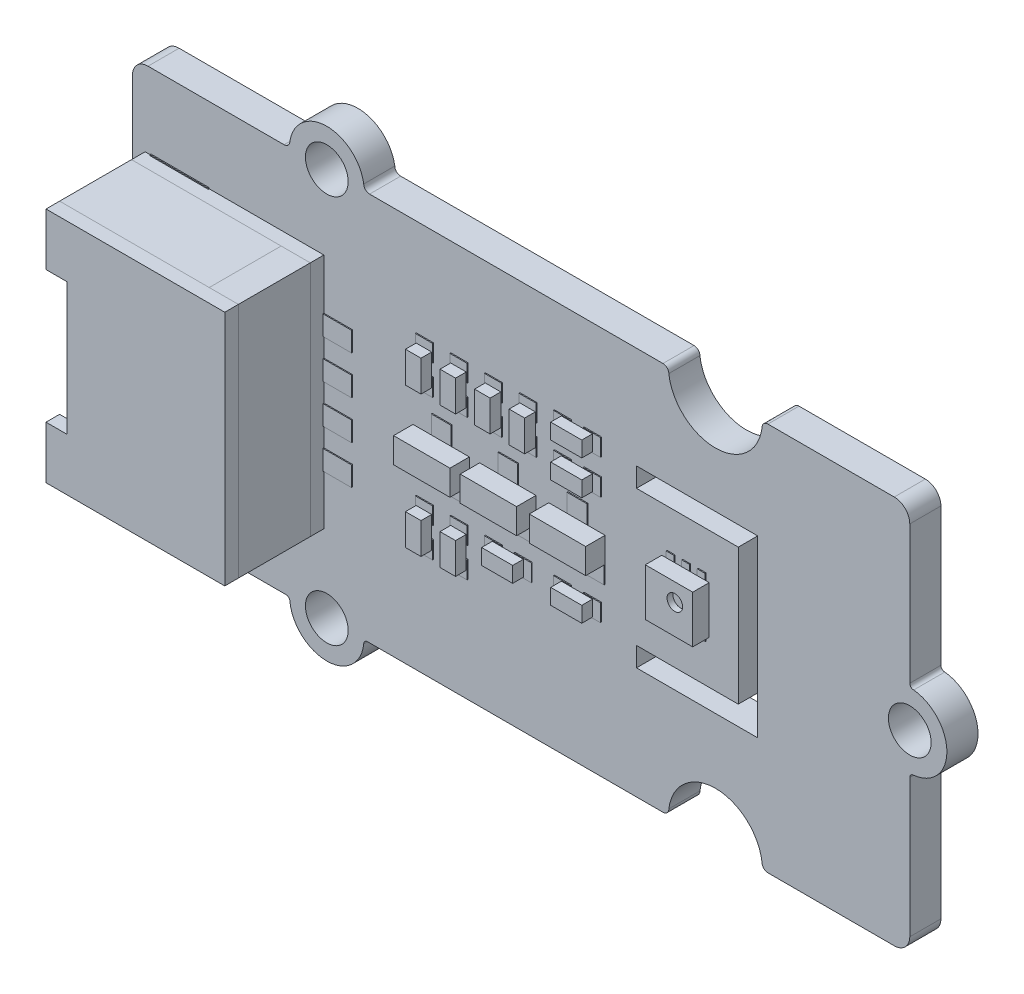
SolidWorks part; units mm, degrees
other "Carte_Grove_101021095"
other "Capteur_SGP40"
ref_plane "Plan de face" through (0, 0, 0) normal (0, 0, 1) x (1, 0, 0)
ref_plane "Plan de dessus" through (0, 0, 0) normal (0, 1, 0) x (1, 0, 0)
ref_plane "Plan de droite" through (0, 0, 0) normal (1, 0, 0) x (0, 0, -1)
sketch "Esquisse1" plane through (0, 0, 0) normal (0, 0, 1) x (1, 0, 0)
  line L0 (19.365, -9.2) -> (19.365, -2.1)
  line L1 (19.365, 2.1) -> (19.365, 9.2)
  line L2 (18.565, 10) -> (12.065, 10)
  line L3 (-19.835, -10) -> (-12.735, -10)
  line L4 (-19.835, 10) -> (-12.835, 10)
  line L5 (-8.435, 10) -> (6.665, 10)
  line L6 (6.665, -10) -> (-8.535, -10)
  line L7 (12.065, -10) -> (18.565, -10)
  line L8 (-20.635, -2.7) -> (-20.635, -9.2)
  line L9 (-20.635, 2.7) -> (-20.635, 9.2)
  line L10 (5.301, 3.754) -> (10.539, 3.754)
  line L11 (10.539, 3.754) -> (10.539, -3.246)
  line L12 (10.539, -3.246) -> (5.301, -3.246)
  line L13 (5.301, -3.246) -> (5.301, -4.246)
  line L14 (5.301, -4.246) -> (11.539, -4.246)
  line L15 (11.539, -4.246) -> (11.539, 4.754)
  line L16 (11.539, 4.754) -> (5.301, 4.754)
  line L17 (5.301, 4.754) -> (5.301, 3.754)
  arc A0 (-19.835, 10) -> (-20.635, 9.2) centre (-19.835, 9.2) ccw
  arc A1 (-20.635, -9.2) -> (-19.835, -10) centre (-19.835, -9.2) ccw
  arc A2 (18.565, -10) -> (19.365, -9.2) centre (18.565, -9.2) ccw
  arc A3 (19.365, 9.2) -> (18.565, 10) centre (18.565, 9.2) ccw
  arc A4 (12.065, 10) -> (11.765, 9.7) centre (12.065, 9.7) ccw
  arc A5 (-12.735, -10) -> (-12.535, -10.2) centre (-12.735, -10.2) cw
  arc A6 (-8.535, -10) -> (-8.735, -10.2) centre (-8.535, -10.2) ccw
  arc A7 (-8.735, -10.2) -> (-12.535, -10.2) centre (-10.635, -10) cw
  arc A8 (-12.835, 10) -> (-12.535, 10.3) centre (-12.835, 10.3) ccw
  arc A9 (6.665, 10) -> (6.965, 9.7) centre (6.665, 9.7) cw
  arc A10 (-8.435, 10) -> (-8.735, 10.3) centre (-8.435, 10.3) cw
  arc A11 (-12.535, 10.3) -> (-8.735, 10.3) centre (-10.635, 10) cw
  arc A12 (6.965, 9.7) -> (11.765, 9.7) centre (9.365, 10) ccw
  arc A13 (19.365, -2.1) -> (19.565, -1.9) centre (19.565, -2.1) cw
  arc A14 (19.365, 2.1) -> (19.565, 1.9) centre (19.565, 2.1) ccw
  arc A15 (19.565, 1.9) -> (19.565, -1.9) centre (19.365, 0) cw
  arc A16 (6.665, -10) -> (6.965, -9.7) centre (6.665, -9.7) ccw
  arc A17 (12.065, -10) -> (11.765, -9.7) centre (12.065, -9.7) cw
  arc A18 (11.765, -9.7) -> (6.965, -9.7) centre (9.365, -10) ccw
  arc A19 (-20.635, 2.7) -> (-20.335, 2.4) centre (-20.335, 2.7) ccw
  arc A20 (-20.635, -2.7) -> (-20.335, -2.4) centre (-20.335, -2.7) cw
  arc A21 (-20.335, -2.4) -> (-20.335, 2.4) centre (-20.635, 0) ccw
  circle A22 centre (-10.635, -10) radius 1.1
  circle A23 centre (-10.635, 10) radius 1.1
  circle A24 centre (19.365, 0) radius 1.1
extrude "PCB_contour_percages_et_isolation_Eagle_ep_ESTIMEE_1_6" add sketch "Esquisse1" along normal blind 1.6 separate body
sketch "Esquisse2" plane through (0, 0, 0) normal (0, 0, 1) x (1, 0, 0)
  line L1 (-19.9848, -6.0898) -> (-10.7848, -6.0898)
  line L2 (-19.9848, -6.0898) -> (-19.9848, 6.1102)
  line L3 (-19.9848, 6.1102) -> (-10.7848, 6.1102)
  line L4 (-10.7848, -6.0898) -> (-10.7848, 6.1102)
extrude "Grove_base_H_ESTIMEE" add sketch "Esquisse2" along normal blind 0.7 from offset 1.6 separate body
sketch "Esquisse3" plane through (0, 0, 0) normal (0, 0, 1) x (1, 0, 0)
  line L1 (-12.2848, -6.0898) -> (-10.7848, -6.0898)
  line L2 (-12.2848, -6.0898) -> (-12.2848, 6.1102)
  line L3 (-12.2848, 6.1102) -> (-10.7848, 6.1102)
  line L4 (-10.7848, -6.0898) -> (-10.7848, 6.1102)
extrude "Grove_dos" add sketch "Esquisse3" along normal blind 3.7 from offset 2.3 separate body
sketch "Esquisse4" plane through (0, 0, 0) normal (0, 0, 1) x (1, 0, 0)
  line L1 (-19.9848, -6.0898) -> (-12.2848, -6.0898)
  line L2 (-19.9848, -6.0898) -> (-19.9848, -5.3898)
  line L3 (-19.9848, -5.3898) -> (-12.2848, -5.3898)
  line L4 (-12.2848, -6.0898) -> (-12.2848, -5.3898)
  line L6 (-19.9848, 5.4102) -> (-12.2848, 5.4102)
  line L7 (-19.9848, 5.4102) -> (-19.9848, 6.1102)
  line L8 (-19.9848, 6.1102) -> (-12.2848, 6.1102)
  line L9 (-12.2848, 5.4102) -> (-12.2848, 6.1102)
extrude "Grove_flancs" add sketch "Esquisse4" along normal blind 3.7 from offset 2.3 separate body
sketch "Esquisse5" plane through (0, 0, 0) normal (0, 0, 1) x (1, 0, 0)
  line L1 (-19.9848, -6.0898) -> (-10.7848, -6.0898)
  line L2 (-19.9848, -6.0898) -> (-19.9848, 6.1102)
  line L3 (-19.9848, 6.1102) -> (-10.7848, 6.1102)
  line L4 (-10.7848, -6.0898) -> (-10.7848, 6.1102)
extrude "Grove_toit" add sketch "Esquisse5" along normal blind 0.7 from offset 6 separate body
sketch "Esquisse6" plane through (0, 0, 0) normal (0, 0, 1) x (1, 0, 0)
  line L1 (-20, -3.39) -> (-18.9, -3.39)
  line L2 (-20, -3.39) -> (-20, 3.41)
  line L3 (-20, 3.41) -> (-18.9, 3.41)
  line L4 (-18.9, -3.39) -> (-18.9, 3.41)
extrude "Encoche_Grove" cut sketch "Esquisse6" against normal blind 0.7 from offset 6.7
sketch "Esquisse7" plane through (0, 0, 0) normal (0, 0, 1) x (1, 0, 0)
  line L1 (-17.8, -3.24) -> (-12.28, -3.24)
  line L2 (-17.8, -3.24) -> (-17.8, -2.74)
  line L3 (-17.8, -2.74) -> (-12.28, -2.74)
  line L4 (-12.28, -3.24) -> (-12.28, -2.74)
  line L6 (-17.8, -1.24) -> (-12.28, -1.24)
  line L7 (-17.8, -1.24) -> (-17.8, -0.74)
  line L8 (-17.8, -0.74) -> (-12.28, -0.74)
  line L9 (-12.28, -1.24) -> (-12.28, -0.74)
  line L11 (-17.8, 0.76) -> (-12.28, 0.76)
  line L12 (-17.8, 0.76) -> (-17.8, 1.26)
  line L13 (-17.8, 1.26) -> (-12.28, 1.26)
  line L14 (-12.28, 0.76) -> (-12.28, 1.26)
  line L16 (-17.8, 2.76) -> (-12.28, 2.76)
  line L17 (-17.8, 2.76) -> (-17.8, 3.26)
  line L18 (-17.8, 3.26) -> (-12.28, 3.26)
  line L19 (-12.28, 2.76) -> (-12.28, 3.26)
extrude "Broches_horizontales_Grove" add sketch "Esquisse7" along normal blind 0.5 from offset 3.4 separate body
sketch "Esquisse8" plane through (0, 0, 0) normal (0, 0, 1) x (1, 0, 0)
  line L1 (6.654, -0.966) -> (9.094, -0.966)
  line L2 (6.654, -0.966) -> (6.654, 1.474)
  line L3 (6.654, 1.474) -> (9.094, 1.474)
  line L4 (9.094, -0.966) -> (9.094, 1.474)
extrude "SGP40_2_44x2_44x0_85" add sketch "Esquisse8" along normal blind 0.85 from offset 1.65 separate body
sketch "Esquisse9" plane through (0, 0, 0) normal (0, 0, 1) x (1, 0, 0)
  circle A0 centre (8.174, 0.554) radius 0.4
extrude "Ouverture_SGP40_diam0_8_profondeur_ESTIMEE" cut sketch "Esquisse9" against normal blind 0.3 from offset 2.5
sketch "Esquisse10" plane through (0, 0, 0) normal (0, 0, 1) x (1, 0, 0)
  line L1 (1.486, 2.521) -> (3.086, 2.521)
  line L2 (1.486, 2.521) -> (1.486, 3.321)
  line L3 (1.486, 3.321) -> (3.086, 3.321)
  line L4 (3.086, 2.521) -> (3.086, 3.321)
extrude "C1_position_Eagle" add sketch "Esquisse10" along normal blind 0.55 from offset 1.65 separate body
sketch "Esquisse11" plane through (0, 0, 0) normal (0, 0, 1) x (1, 0, 0)
  line L1 (1.486, 4.299) -> (3.086, 4.299)
  line L2 (1.486, 4.299) -> (1.486, 5.099)
  line L3 (1.486, 5.099) -> (3.086, 5.099)
  line L4 (3.086, 4.299) -> (3.086, 5.099)
extrude "C2_position_Eagle" add sketch "Esquisse11" along normal blind 0.55 from offset 1.65 separate body
sketch "Esquisse12" plane through (0, 0, 0) normal (0, 0, 1) x (1, 0, 0)
  line L1 (-6.149, -0.396) -> (-3.249, -0.396)
  line L2 (-6.149, -0.396) -> (-6.149, 0.904)
  line L3 (-6.149, 0.904) -> (-3.249, 0.904)
  line L4 (-3.249, -0.396) -> (-3.249, 0.904)
extrude "U2_position_Eagle" add sketch "Esquisse12" along normal blind 1 from offset 1.65 separate body
sketch "Esquisse13" plane through (0, 0, 0) normal (0, 0, 1) x (1, 0, 0)
  line L1 (-5.988, 3.01) -> (-5.188, 3.01)
  line L2 (-5.988, 3.01) -> (-5.988, 4.61)
  line L3 (-5.988, 4.61) -> (-5.188, 4.61)
  line L4 (-5.188, 3.01) -> (-5.188, 4.61)
extrude "C3_position_Eagle" add sketch "Esquisse13" along normal blind 0.55 from offset 1.65 separate body
sketch "Esquisse14" plane through (0, 0, 0) normal (0, 0, 1) x (1, 0, 0)
  line L1 (-4.21, 3.01) -> (-3.41, 3.01)
  line L2 (-4.21, 3.01) -> (-4.21, 4.61)
  line L3 (-4.21, 4.61) -> (-3.41, 4.61)
  line L4 (-3.41, 3.01) -> (-3.41, 4.61)
extrude "C4_position_Eagle" add sketch "Esquisse14" along normal blind 0.55 from offset 1.65 separate body
sketch "Esquisse15" plane through (0, 0, 0) normal (0, 0, 1) x (1, 0, 0)
  line L1 (-5.988, -4.229) -> (-5.188, -4.229)
  line L2 (-5.988, -4.229) -> (-5.988, -2.629)
  line L3 (-5.988, -2.629) -> (-5.188, -2.629)
  line L4 (-5.188, -4.229) -> (-5.188, -2.629)
extrude "C5_position_Eagle" add sketch "Esquisse15" along normal blind 0.55 from offset 1.65 separate body
sketch "Esquisse16" plane through (0, 0, 0) normal (0, 0, 1) x (1, 0, 0)
  line L1 (-4.21, -4.229) -> (-3.41, -4.229)
  line L2 (-4.21, -4.229) -> (-4.21, -2.629)
  line L3 (-4.21, -2.629) -> (-3.41, -2.629)
  line L4 (-3.41, -4.229) -> (-3.41, -2.629)
extrude "C6_position_Eagle" add sketch "Esquisse16" along normal blind 0.55 from offset 1.65 separate body
sketch "Esquisse17" plane through (0, 0, 0) normal (0, 0, 1) x (1, 0, 0)
  line L1 (-2.72, -0.396) -> (0.18, -0.396)
  line L2 (-2.72, -0.396) -> (-2.72, 0.904)
  line L3 (-2.72, 0.904) -> (0.18, 0.904)
  line L4 (0.18, -0.396) -> (0.18, 0.904)
extrude "Q7_position_Eagle" add sketch "Esquisse17" along normal blind 1 from offset 1.65 separate body
sketch "Esquisse18" plane through (0, 0, 0) normal (0, 0, 1) x (1, 0, 0)
  line L1 (0.836, -0.396) -> (3.736, -0.396)
  line L2 (0.836, -0.396) -> (0.836, 0.904)
  line L3 (0.836, 0.904) -> (3.736, 0.904)
  line L4 (3.736, -0.396) -> (3.736, 0.904)
extrude "Q8_position_Eagle" add sketch "Esquisse18" along normal blind 1 from offset 1.65 separate body
sketch "Esquisse19" plane through (0, 0, 0) normal (0, 0, 1) x (1, 0, 0)
  line L1 (1.486, -3.067) -> (3.086, -3.067)
  line L2 (1.486, -3.067) -> (1.486, -2.267)
  line L3 (1.486, -2.267) -> (3.086, -2.267)
  line L4 (3.086, -3.067) -> (3.086, -2.267)
extrude "R20_position_Eagle" add sketch "Esquisse19" along normal blind 0.55 from offset 1.65 separate body
sketch "Esquisse20" plane through (0, 0, 0) normal (0, 0, 1) x (1, 0, 0)
  line L1 (-2.07, -3.067) -> (-0.47, -3.067)
  line L2 (-2.07, -3.067) -> (-2.07, -2.267)
  line L3 (-2.07, -2.267) -> (-0.47, -2.267)
  line L4 (-0.47, -3.067) -> (-0.47, -2.267)
extrude "R21_position_Eagle" add sketch "Esquisse20" along normal blind 0.55 from offset 1.65 separate body
sketch "Esquisse21" plane through (0, 0, 0) normal (0, 0, 1) x (1, 0, 0)
  line L1 (-0.654, 3.01) -> (0.146, 3.01)
  line L2 (-0.654, 3.01) -> (-0.654, 4.61)
  line L3 (-0.654, 4.61) -> (0.146, 4.61)
  line L4 (0.146, 3.01) -> (0.146, 4.61)
extrude "R22_position_Eagle" add sketch "Esquisse21" along normal blind 0.55 from offset 1.65 separate body
sketch "Esquisse22" plane through (0, 0, 0) normal (0, 0, 1) x (1, 0, 0)
  line L1 (-2.432, 3.01) -> (-1.632, 3.01)
  line L2 (-2.432, 3.01) -> (-2.432, 4.61)
  line L3 (-2.432, 4.61) -> (-1.632, 4.61)
  line L4 (-1.632, 3.01) -> (-1.632, 4.61)
extrude "R23_position_Eagle" add sketch "Esquisse22" along normal blind 0.55 from offset 1.65 separate body
sketch "Esquisse23" plane through (0, 0, 0) normal (0, 0, 1) x (1, 0, 0)
  line L1 (2.6035, 2.4765) -> (3.4925, 2.4765)
  line L2 (2.6035, 2.4765) -> (2.6035, 3.3655)
  line L3 (2.6035, 3.3655) -> (3.4925, 3.3655)
  line L4 (3.4925, 2.4765) -> (3.4925, 3.3655)
extrude "Pad_C1_0" add sketch "Esquisse23" along normal blind 0.05 from offset 1.6 separate body
sketch "Esquisse24" plane through (0, 0, 0) normal (0, 0, 1) x (1, 0, 0)
  line L1 (1.0795, 2.4765) -> (1.9685, 2.4765)
  line L2 (1.0795, 2.4765) -> (1.0795, 3.3655)
  line L3 (1.0795, 3.3655) -> (1.9685, 3.3655)
  line L4 (1.9685, 2.4765) -> (1.9685, 3.3655)
extrude "Pad_C1_1" add sketch "Esquisse24" along normal blind 0.05 from offset 1.6 separate body
sketch "Esquisse25" plane through (0, 0, 0) normal (0, 0, 1) x (1, 0, 0)
  line L1 (2.6035, 4.2545) -> (3.4925, 4.2545)
  line L2 (2.6035, 4.2545) -> (2.6035, 5.1435)
  line L3 (2.6035, 5.1435) -> (3.4925, 5.1435)
  line L4 (3.4925, 4.2545) -> (3.4925, 5.1435)
extrude "Pad_C2_0" add sketch "Esquisse25" along normal blind 0.05 from offset 1.6 separate body
sketch "Esquisse26" plane through (0, 0, 0) normal (0, 0, 1) x (1, 0, 0)
  line L1 (1.0795, 4.2545) -> (1.9685, 4.2545)
  line L2 (1.0795, 4.2545) -> (1.0795, 5.1435)
  line L3 (1.0795, 5.1435) -> (1.9685, 5.1435)
  line L4 (1.9685, 4.2545) -> (1.9685, 5.1435)
extrude "Pad_C2_1" add sketch "Esquisse26" along normal blind 0.05 from offset 1.6 separate body
sketch "Esquisse27" plane through (0, 0, 0) normal (0, 0, 1) x (1, 0, 0)
  line L1 (-12.0548, -3.4948) -> (-9.3148, -3.4948)
  line L2 (-12.0548, -3.4948) -> (-12.0548, -2.4848)
  line L3 (-12.0548, -2.4848) -> (-9.3148, -2.4848)
  line L4 (-9.3148, -3.4948) -> (-9.3148, -2.4848)
extrude "Pad_J1_0" add sketch "Esquisse27" along normal blind 0.05 from offset 1.6 separate body
sketch "Esquisse28" plane through (0, 0, 0) normal (0, 0, 1) x (1, 0, 0)
  line L1 (-12.0548, -1.4948) -> (-9.3148, -1.4948)
  line L2 (-12.0548, -1.4948) -> (-12.0548, -0.4848)
  line L3 (-12.0548, -0.4848) -> (-9.3148, -0.4848)
  line L4 (-9.3148, -1.4948) -> (-9.3148, -0.4848)
extrude "Pad_J1_1" add sketch "Esquisse28" along normal blind 0.05 from offset 1.6 separate body
sketch "Esquisse29" plane through (0, 0, 0) normal (0, 0, 1) x (1, 0, 0)
  line L1 (-12.0548, 0.5052) -> (-9.3148, 0.5052)
  line L2 (-12.0548, 0.5052) -> (-12.0548, 1.5152)
  line L3 (-12.0548, 1.5152) -> (-9.3148, 1.5152)
  line L4 (-9.3148, 0.5052) -> (-9.3148, 1.5152)
extrude "Pad_J1_2" add sketch "Esquisse29" along normal blind 0.05 from offset 1.6 separate body
sketch "Esquisse30" plane through (0, 0, 0) normal (0, 0, 1) x (1, 0, 0)
  line L1 (-12.0548, 2.5052) -> (-9.3148, 2.5052)
  line L2 (-12.0548, 2.5052) -> (-12.0548, 3.5152)
  line L3 (-12.0548, 3.5152) -> (-9.3148, 3.5152)
  line L4 (-9.3148, 2.5052) -> (-9.3148, 3.5152)
extrude "Pad_J1_3" add sketch "Esquisse30" along normal blind 0.05 from offset 1.6 separate body
sketch "Esquisse31" plane through (0, 0, 0) normal (0, 0, 1) x (1, 0, 0)
  line L1 (-19.6848, -6.1398) -> (-16.6848, -6.1398)
  line L2 (-19.6848, -6.1398) -> (-19.6848, -4.6398)
  line L3 (-19.6848, -4.6398) -> (-16.6848, -4.6398)
  line L4 (-16.6848, -6.1398) -> (-16.6848, -4.6398)
extrude "Pad_J1_4" add sketch "Esquisse31" along normal blind 0.05 from offset 1.6 separate body
sketch "Esquisse32" plane through (0, 0, 0) normal (0, 0, 1) x (1, 0, 0)
  line L1 (-19.6848, 4.6602) -> (-16.6848, 4.6602)
  line L2 (-19.6848, 4.6602) -> (-19.6848, 6.1602)
  line L3 (-19.6848, 6.1602) -> (-16.6848, 6.1602)
  line L4 (-16.6848, 4.6602) -> (-16.6848, 6.1602)
extrude "Pad_J1_5" add sketch "Esquisse32" along normal blind 0.05 from offset 1.6 separate body
sketch "Esquisse33" plane through (0, 0, 0) normal (0, 0, 1) x (1, 0, 0)
  line L1 (-5.207, 0.6985) -> (-4.191, 0.6985)
  line L2 (-5.207, 0.6985) -> (-5.207, 1.8415)
  line L3 (-5.207, 1.8415) -> (-4.191, 1.8415)
  line L4 (-4.191, 0.6985) -> (-4.191, 1.8415)
extrude "Pad_U2_0" add sketch "Esquisse33" along normal blind 0.05 from offset 1.6 separate body
sketch "Esquisse34" plane through (0, 0, 0) normal (0, 0, 1) x (1, 0, 0)
  line L1 (-4.318, -1.3335) -> (-3.302, -1.3335)
  line L2 (-4.318, -1.3335) -> (-4.318, -0.1905)
  line L3 (-4.318, -0.1905) -> (-3.302, -0.1905)
  line L4 (-3.302, -1.3335) -> (-3.302, -0.1905)
extrude "Pad_U2_1" add sketch "Esquisse34" along normal blind 0.05 from offset 1.6 separate body
sketch "Esquisse35" plane through (0, 0, 0) normal (0, 0, 1) x (1, 0, 0)
  line L1 (-6.096, -1.3335) -> (-5.08, -1.3335)
  line L2 (-6.096, -1.3335) -> (-6.096, -0.1905)
  line L3 (-6.096, -0.1905) -> (-5.08, -0.1905)
  line L4 (-5.08, -1.3335) -> (-5.08, -0.1905)
extrude "Pad_U2_2" add sketch "Esquisse35" along normal blind 0.05 from offset 1.6 separate body
sketch "Esquisse36" plane through (0, 0, 0) normal (0, 0, 1) x (1, 0, 0)
  line L1 (-6.0325, 2.6035) -> (-5.1435, 2.6035)
  line L2 (-6.0325, 2.6035) -> (-6.0325, 3.4925)
  line L3 (-6.0325, 3.4925) -> (-5.1435, 3.4925)
  line L4 (-5.1435, 2.6035) -> (-5.1435, 3.4925)
extrude "Pad_C3_0" add sketch "Esquisse36" along normal blind 0.05 from offset 1.6 separate body
sketch "Esquisse37" plane through (0, 0, 0) normal (0, 0, 1) x (1, 0, 0)
  line L1 (-6.0325, 4.1275) -> (-5.1435, 4.1275)
  line L2 (-6.0325, 4.1275) -> (-6.0325, 5.0165)
  line L3 (-6.0325, 5.0165) -> (-5.1435, 5.0165)
  line L4 (-5.1435, 4.1275) -> (-5.1435, 5.0165)
extrude "Pad_C3_1" add sketch "Esquisse37" along normal blind 0.05 from offset 1.6 separate body
sketch "Esquisse38" plane through (0, 0, 0) normal (0, 0, 1) x (1, 0, 0)
  line L1 (-4.2545, 2.6035) -> (-3.3655, 2.6035)
  line L2 (-4.2545, 2.6035) -> (-4.2545, 3.4925)
  line L3 (-4.2545, 3.4925) -> (-3.3655, 3.4925)
  line L4 (-3.3655, 2.6035) -> (-3.3655, 3.4925)
extrude "Pad_C4_0" add sketch "Esquisse38" along normal blind 0.05 from offset 1.6 separate body
sketch "Esquisse39" plane through (0, 0, 0) normal (0, 0, 1) x (1, 0, 0)
  line L1 (-4.2545, 4.1275) -> (-3.3655, 4.1275)
  line L2 (-4.2545, 4.1275) -> (-4.2545, 5.0165)
  line L3 (-4.2545, 5.0165) -> (-3.3655, 5.0165)
  line L4 (-3.3655, 4.1275) -> (-3.3655, 5.0165)
extrude "Pad_C4_1" add sketch "Esquisse39" along normal blind 0.05 from offset 1.6 separate body
sketch "Esquisse40" plane through (0, 0, 0) normal (0, 0, 1) x (1, 0, 0)
  line L1 (-6.0325, -3.1115) -> (-5.1435, -3.1115)
  line L2 (-6.0325, -3.1115) -> (-6.0325, -2.2225)
  line L3 (-6.0325, -2.2225) -> (-5.1435, -2.2225)
  line L4 (-5.1435, -3.1115) -> (-5.1435, -2.2225)
extrude "Pad_C5_0" add sketch "Esquisse40" along normal blind 0.05 from offset 1.6 separate body
sketch "Esquisse41" plane through (0, 0, 0) normal (0, 0, 1) x (1, 0, 0)
  line L1 (-6.0325, -4.6355) -> (-5.1435, -4.6355)
  line L2 (-6.0325, -4.6355) -> (-6.0325, -3.7465)
  line L3 (-6.0325, -3.7465) -> (-5.1435, -3.7465)
  line L4 (-5.1435, -4.6355) -> (-5.1435, -3.7465)
extrude "Pad_C5_1" add sketch "Esquisse41" along normal blind 0.05 from offset 1.6 separate body
sketch "Esquisse42" plane through (0, 0, 0) normal (0, 0, 1) x (1, 0, 0)
  line L1 (-4.2545, -3.1115) -> (-3.3655, -3.1115)
  line L2 (-4.2545, -3.1115) -> (-4.2545, -2.2225)
  line L3 (-4.2545, -2.2225) -> (-3.3655, -2.2225)
  line L4 (-3.3655, -3.1115) -> (-3.3655, -2.2225)
extrude "Pad_C6_0" add sketch "Esquisse42" along normal blind 0.05 from offset 1.6 separate body
sketch "Esquisse43" plane through (0, 0, 0) normal (0, 0, 1) x (1, 0, 0)
  line L1 (-4.2545, -4.6355) -> (-3.3655, -4.6355)
  line L2 (-4.2545, -4.6355) -> (-4.2545, -3.7465)
  line L3 (-4.2545, -3.7465) -> (-3.3655, -3.7465)
  line L4 (-3.3655, -4.6355) -> (-3.3655, -3.7465)
extrude "Pad_C6_1" add sketch "Esquisse43" along normal blind 0.05 from offset 1.6 separate body
sketch "Esquisse44" plane through (0, 0, 0) normal (0, 0, 1) x (1, 0, 0)
  line L1 (-1.778, 0.6985) -> (-0.762, 0.6985)
  line L2 (-1.778, 0.6985) -> (-1.778, 1.8415)
  line L3 (-1.778, 1.8415) -> (-0.762, 1.8415)
  line L4 (-0.762, 0.6985) -> (-0.762, 1.8415)
extrude "Pad_Q7_0" add sketch "Esquisse44" along normal blind 0.05 from offset 1.6 separate body
sketch "Esquisse45" plane through (0, 0, 0) normal (0, 0, 1) x (1, 0, 0)
  line L1 (-0.889, -1.3335) -> (0.127, -1.3335)
  line L2 (-0.889, -1.3335) -> (-0.889, -0.1905)
  line L3 (-0.889, -0.1905) -> (0.127, -0.1905)
  line L4 (0.127, -1.3335) -> (0.127, -0.1905)
extrude "Pad_Q7_1" add sketch "Esquisse45" along normal blind 0.05 from offset 1.6 separate body
sketch "Esquisse46" plane through (0, 0, 0) normal (0, 0, 1) x (1, 0, 0)
  line L1 (-2.667, -1.3335) -> (-1.651, -1.3335)
  line L2 (-2.667, -1.3335) -> (-2.667, -0.1905)
  line L3 (-2.667, -0.1905) -> (-1.651, -0.1905)
  line L4 (-1.651, -1.3335) -> (-1.651, -0.1905)
extrude "Pad_Q7_2" add sketch "Esquisse46" along normal blind 0.05 from offset 1.6 separate body
sketch "Esquisse47" plane through (0, 0, 0) normal (0, 0, 1) x (1, 0, 0)
  line L1 (1.778, 0.6985) -> (2.794, 0.6985)
  line L2 (1.778, 0.6985) -> (1.778, 1.8415)
  line L3 (1.778, 1.8415) -> (2.794, 1.8415)
  line L4 (2.794, 0.6985) -> (2.794, 1.8415)
extrude "Pad_Q8_0" add sketch "Esquisse47" along normal blind 0.05 from offset 1.6 separate body
sketch "Esquisse48" plane through (0, 0, 0) normal (0, 0, 1) x (1, 0, 0)
  line L1 (2.667, -1.3335) -> (3.683, -1.3335)
  line L2 (2.667, -1.3335) -> (2.667, -0.1905)
  line L3 (2.667, -0.1905) -> (3.683, -0.1905)
  line L4 (3.683, -1.3335) -> (3.683, -0.1905)
extrude "Pad_Q8_1" add sketch "Esquisse48" along normal blind 0.05 from offset 1.6 separate body
sketch "Esquisse49" plane through (0, 0, 0) normal (0, 0, 1) x (1, 0, 0)
  line L1 (0.889, -1.3335) -> (1.905, -1.3335)
  line L2 (0.889, -1.3335) -> (0.889, -0.1905)
  line L3 (0.889, -0.1905) -> (1.905, -0.1905)
  line L4 (1.905, -1.3335) -> (1.905, -0.1905)
extrude "Pad_Q8_2" add sketch "Esquisse49" along normal blind 0.05 from offset 1.6 separate body
sketch "Esquisse50" plane through (0, 0, 0) normal (0, 0, 1) x (1, 0, 0)
  line L1 (1.0795, -3.1115) -> (1.9685, -3.1115)
  line L2 (1.0795, -3.1115) -> (1.0795, -2.2225)
  line L3 (1.0795, -2.2225) -> (1.9685, -2.2225)
  line L4 (1.9685, -3.1115) -> (1.9685, -2.2225)
extrude "Pad_R20_0" add sketch "Esquisse50" along normal blind 0.05 from offset 1.6 separate body
sketch "Esquisse51" plane through (0, 0, 0) normal (0, 0, 1) x (1, 0, 0)
  line L1 (2.6035, -3.1115) -> (3.4925, -3.1115)
  line L2 (2.6035, -3.1115) -> (2.6035, -2.2225)
  line L3 (2.6035, -2.2225) -> (3.4925, -2.2225)
  line L4 (3.4925, -3.1115) -> (3.4925, -2.2225)
extrude "Pad_R20_1" add sketch "Esquisse51" along normal blind 0.05 from offset 1.6 separate body
sketch "Esquisse52" plane through (0, 0, 0) normal (0, 0, 1) x (1, 0, 0)
  line L1 (-2.4765, -3.1115) -> (-1.5875, -3.1115)
  line L2 (-2.4765, -3.1115) -> (-2.4765, -2.2225)
  line L3 (-2.4765, -2.2225) -> (-1.5875, -2.2225)
  line L4 (-1.5875, -3.1115) -> (-1.5875, -2.2225)
extrude "Pad_R21_0" add sketch "Esquisse52" along normal blind 0.05 from offset 1.6 separate body
sketch "Esquisse53" plane through (0, 0, 0) normal (0, 0, 1) x (1, 0, 0)
  line L1 (-0.9525, -3.1115) -> (-0.0635, -3.1115)
  line L2 (-0.9525, -3.1115) -> (-0.9525, -2.2225)
  line L3 (-0.9525, -2.2225) -> (-0.0635, -2.2225)
  line L4 (-0.0635, -3.1115) -> (-0.0635, -2.2225)
extrude "Pad_R21_1" add sketch "Esquisse53" along normal blind 0.05 from offset 1.6 separate body
sketch "Esquisse54" plane through (0, 0, 0) normal (0, 0, 1) x (1, 0, 0)
  line L1 (-0.6985, 4.1275) -> (0.1905, 4.1275)
  line L2 (-0.6985, 4.1275) -> (-0.6985, 5.0165)
  line L3 (-0.6985, 5.0165) -> (0.1905, 5.0165)
  line L4 (0.1905, 4.1275) -> (0.1905, 5.0165)
extrude "Pad_R22_0" add sketch "Esquisse54" along normal blind 0.05 from offset 1.6 separate body
sketch "Esquisse55" plane through (0, 0, 0) normal (0, 0, 1) x (1, 0, 0)
  line L1 (-0.6985, 2.6035) -> (0.1905, 2.6035)
  line L2 (-0.6985, 2.6035) -> (-0.6985, 3.4925)
  line L3 (-0.6985, 3.4925) -> (0.1905, 3.4925)
  line L4 (0.1905, 2.6035) -> (0.1905, 3.4925)
extrude "Pad_R22_1" add sketch "Esquisse55" along normal blind 0.05 from offset 1.6 separate body
sketch "Esquisse56" plane through (0, 0, 0) normal (0, 0, 1) x (1, 0, 0)
  line L1 (-2.4765, 4.1275) -> (-1.5875, 4.1275)
  line L2 (-2.4765, 4.1275) -> (-2.4765, 5.0165)
  line L3 (-2.4765, 5.0165) -> (-1.5875, 5.0165)
  line L4 (-1.5875, 4.1275) -> (-1.5875, 5.0165)
extrude "Pad_R23_0" add sketch "Esquisse56" along normal blind 0.05 from offset 1.6 separate body
sketch "Esquisse57" plane through (0, 0, 0) normal (0, 0, 1) x (1, 0, 0)
  line L1 (-2.4765, 2.6035) -> (-1.5875, 2.6035)
  line L2 (-2.4765, 2.6035) -> (-2.4765, 3.4925)
  line L3 (-2.4765, 3.4925) -> (-1.5875, 3.4925)
  line L4 (-1.5875, 2.6035) -> (-1.5875, 3.4925)
extrude "Pad_R23_1" add sketch "Esquisse57" along normal blind 0.05 from offset 1.6 separate body
sketch "Esquisse58" plane through (0, 0, 0) normal (0, 0, 1) x (1, 0, 0)
  line L1 (6.874, -1.271) -> (7.274, -1.271)
  line L2 (6.874, -1.271) -> (6.874, -0.621)
  line L3 (6.874, -0.621) -> (7.274, -0.621)
  line L4 (7.274, -1.271) -> (7.274, -0.621)
extrude "Pad_U1_0" add sketch "Esquisse58" along normal blind 0.05 from offset 1.6 separate body
sketch "Esquisse59" plane through (0, 0, 0) normal (0, 0, 1) x (1, 0, 0)
  line L1 (7.674, -1.271) -> (8.074, -1.271)
  line L2 (7.674, -1.271) -> (7.674, -0.621)
  line L3 (7.674, -0.621) -> (8.074, -0.621)
  line L4 (8.074, -1.271) -> (8.074, -0.621)
extrude "Pad_U1_1" add sketch "Esquisse59" along normal blind 0.05 from offset 1.6 separate body
sketch "Esquisse60" plane through (0, 0, 0) normal (0, 0, 1) x (1, 0, 0)
  line L1 (8.474, -1.271) -> (8.874, -1.271)
  line L2 (8.474, -1.271) -> (8.474, -0.621)
  line L3 (8.474, -0.621) -> (8.874, -0.621)
  line L4 (8.874, -1.271) -> (8.874, -0.621)
extrude "Pad_U1_2" add sketch "Esquisse60" along normal blind 0.05 from offset 1.6 separate body
sketch "Esquisse61" plane through (0, 0, 0) normal (0, 0, 1) x (1, 0, 0)
  line L1 (8.474, 1.129) -> (8.874, 1.129)
  line L2 (8.474, 1.129) -> (8.474, 1.779)
  line L3 (8.474, 1.779) -> (8.874, 1.779)
  line L4 (8.874, 1.129) -> (8.874, 1.779)
extrude "Pad_U1_3" add sketch "Esquisse61" along normal blind 0.05 from offset 1.6 separate body
sketch "Esquisse62" plane through (0, 0, 0) normal (0, 0, 1) x (1, 0, 0)
  line L1 (7.674, 1.129) -> (8.074, 1.129)
  line L2 (7.674, 1.129) -> (7.674, 1.779)
  line L3 (7.674, 1.779) -> (8.074, 1.779)
  line L4 (8.074, 1.129) -> (8.074, 1.779)
extrude "Pad_U1_4" add sketch "Esquisse62" along normal blind 0.05 from offset 1.6 separate body
sketch "Esquisse63" plane through (0, 0, 0) normal (0, 0, 1) x (1, 0, 0)
  line L1 (6.874, 1.129) -> (7.274, 1.129)
  line L2 (6.874, 1.129) -> (6.874, 1.779)
  line L3 (6.874, 1.779) -> (7.274, 1.779)
  line L4 (7.274, 1.129) -> (7.274, 1.779)
extrude "Pad_U1_5" add sketch "Esquisse63" along normal blind 0.05 from offset 1.6 separate body
sketch "Esquisse64" plane through (0, 0, 0) normal (0, 0, 1) x (1, 0, 0)
  line L1 (7.124, -0.271) -> (8.624, -0.271)
  line L2 (7.124, -0.271) -> (7.124, 0.779)
  line L3 (7.124, 0.779) -> (8.624, 0.779)
  line L4 (8.624, -0.271) -> (8.624, 0.779)
extrude "Pad_U1_6" add sketch "Esquisse64" along normal blind 0.05 from offset 1.6 separate body
